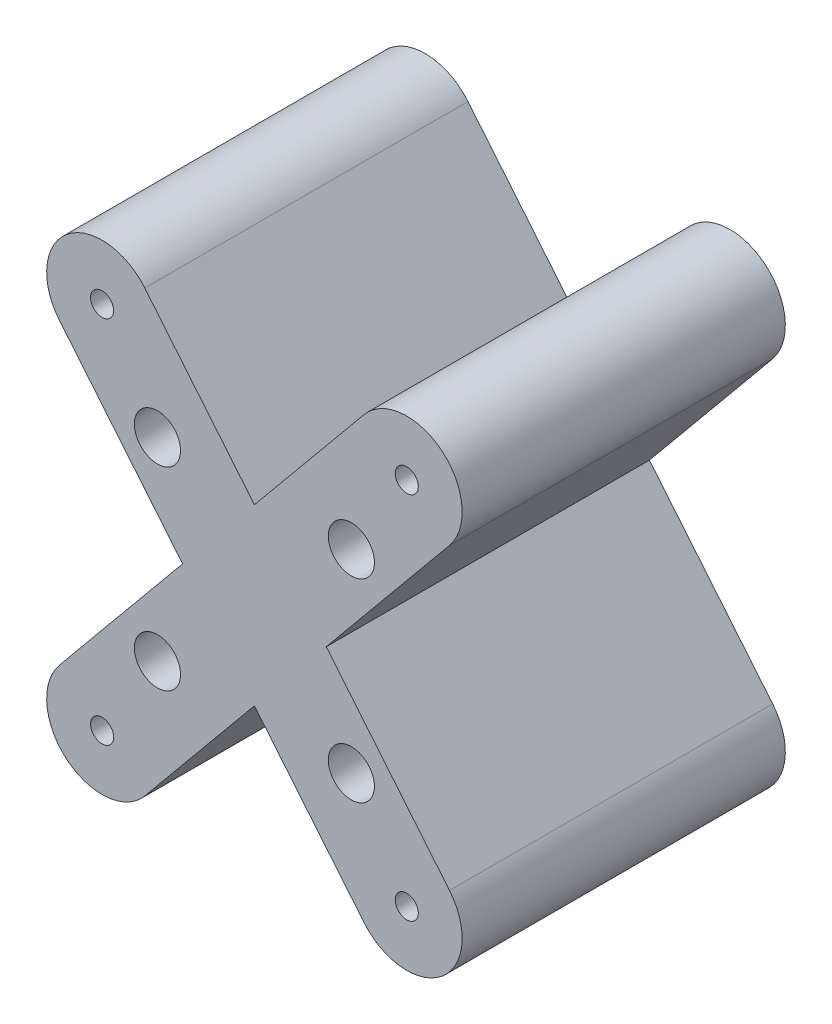
SolidWorks part; units mm, degrees
ref_plane "Front Plane" through (0, 0, 0) normal (0, 0, 1) x (1, 0, 0)
ref_plane "Top Plane" through (0, 0, 0) normal (0, 1, 0) x (1, 0, 0)
ref_plane "Right Plane" through (0, 0, 0) normal (1, 0, 0) x (0, 0, -1)
sketch "Sketch1" plane through (0, 0, 0) normal (0, 0, 1) x (1, 0, 0)
  line L0 (33, 40) -> (-33, -40) construction
  line L5 (-33, 40) -> (33, -40) construction
  line L6 (-33, -40) -> (33, 40) construction
  line L11 (-21, 21) -> (21, -21) construction
  line L12 (-21, -21) -> (21, 21) construction
  line L13 (42.2565, 32.3634) -> (15.5567, 0)
  line L14 (23.7435, 47.6366) -> (0, 18.8566)
  line L15 (33, -40) -> (-33, 40) construction
  line L16 (23.7435, -47.6366) -> (0, -18.8566)
  line L17 (42.2565, -32.3634) -> (15.5567, 0)
  line L18 (0, -18.8566) -> (-23.7435, -47.6366)
  line L19 (0, 18.8566) -> (-23.7435, 47.6366)
  line L20 (-15.5567, 0) -> (-42.2565, 32.3634)
  line L22 (-15.5567, 0) -> (-42.2565, -32.3634)
  arc A0 (42.2565, 32.3634) -> (23.7435, 47.6366) centre (33, 40) ccw
  arc A1 (-42.2565, -32.3634) -> (-23.7435, -47.6366) centre (-33, -40) ccw
  arc A2 (23.7435, -47.6366) -> (42.2565, -32.3634) centre (33, -40) ccw
  arc A3 (-23.7435, 47.6366) -> (-42.2565, 32.3634) centre (-33, 40) ccw
  circle A4 centre (-33, 40) radius 2.5
  circle A5 centre (33, 40) radius 2.5
  circle A6 centre (-21, 21) radius 2.5
  circle A7 centre (21, 21) radius 2.5
  circle A8 centre (21, -21) radius 2.5
  circle A9 centre (-21, -21) radius 2.5
  circle A10 centre (-33, -40) radius 2.5
  circle A11 centre (33, -40) radius 2.5
  point P0 (0, 0)
  point P6 (0, 0)
  point P11 (0, 0)
  point P16 (0, 0)
  dimension "D7" = 5
  dimension "D8" = 5
  dimension "D9" = 5
  dimension "D10" = 5
  dimension "D11" = 5
  dimension "D12" = 5
  dimension "D13" = 5
  dimension "D14" = 5
  dimension "D1" = 42
  dimension "D2" = 42
  dimension "D3" = 66
  dimension "D4" = 80
  dimension "D5" = 24
  dimension "D6" = 24
extrude "Boss-Extrude1" add sketch "Sketch1" along normal blind 70
sketch "Sketch2" plane through (0, 0, 70) normal (0, 0, 1) x (1, 0, 0)
  circle A0 centre (-21, -21) radius 5
  circle A1 centre (-21, 21) radius 5
  circle A2 centre (21, 21) radius 5
  circle A3 centre (21, -21) radius 5
  dimension "D1" = 10
  dimension "D2" = 10
  dimension "D3" = 10
  dimension "D4" = 10
extrude "Cut-Extrude1" cut sketch "Sketch2" against normal blind 60
sketch "Sketch3" plane through (0, 0, 0) normal (0, 0, -1) x (-1, 0, 0)
  circle A0 centre (33, 40) radius 6
  circle A1 centre (33, -40) radius 6
  circle A2 centre (-33, 40) radius 6
  circle A3 centre (-33, -40) radius 6
  dimension "D1" = 12
  dimension "D2" = 12
  dimension "D3" = 12
  dimension "D4" = 12
extrude "Cut-Extrude2" cut sketch "Sketch3" against normal blind 65
